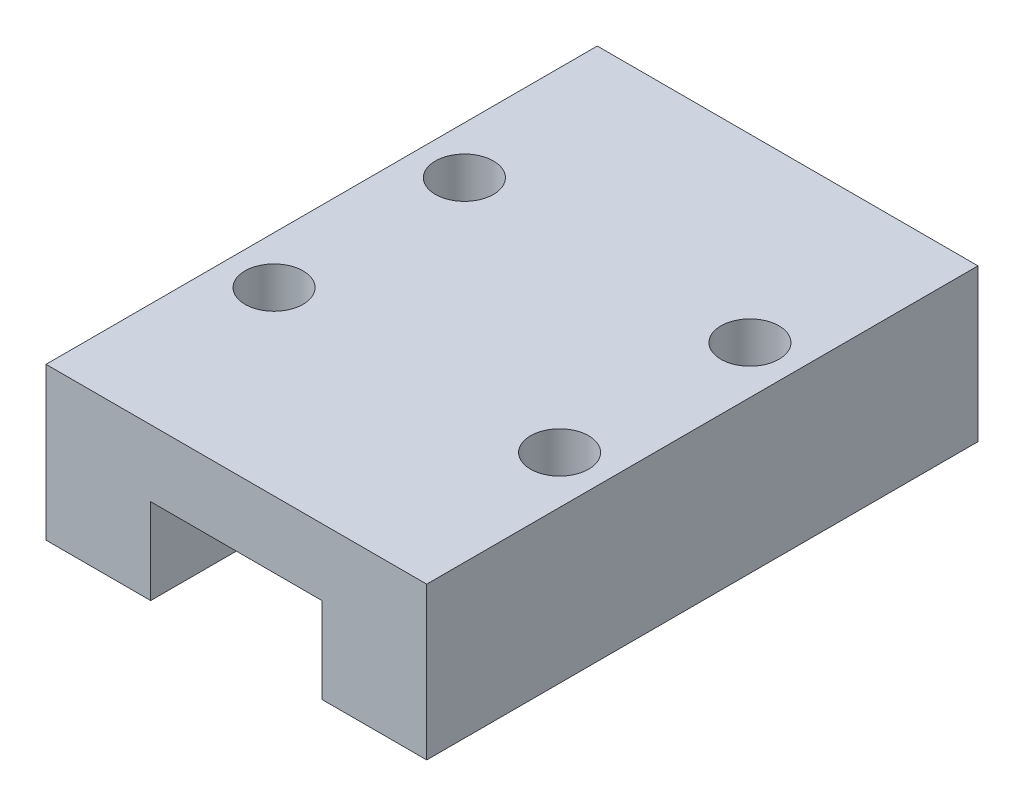
SolidWorks part; units mm, degrees
ref_plane "前视基准面" through (0, 0, 0) normal (0, 0, 1) x (1, 0, 0)
ref_plane "上视基准面" through (0, 0, 0) normal (0, 1, 0) x (1, 0, 0)
ref_plane "右视基准面" through (0, 0, 0) normal (1, 0, 0) x (0, 0, -1)
other "Configuration Table"
sketch "草图1" plane through (0, 0, 0) normal (0, 0, 1) x (1, 0, 0)
  line L0 (0, 0) -> (0, 4.5) construction
  line L1 (0, 4.5) -> (0, 8) construction
  line L2 (-10, 8) -> (10, 8)
  line L3 (10, 8) -> (10, 0)
  line L4 (10, 0) -> (4.5, 0)
  line L5 (4.5, 0) -> (4.5, 4.5)
  line L6 (4.5, 4.5) -> (-4.5, 4.5)
  line L7 (0, 0) -> (4.5, 0) construction
  line L8 (-10, 8) -> (-10, 0)
  line L9 (-10, 0) -> (-4.5, 0)
  line L10 (-4.5, 0) -> (-4.5, 4.5)
  line L11 (-4.5, 0) -> (-4.5, -2) construction
  line L12 (-4.5, -2) -> (4.5, -2) construction
  line L13 (4.5, -2) -> (4.5, 0) construction
  dimension "D1" = 20
  dimension "D2" = 9
  dimension "D3" = 8
  dimension "D4" = 10
  dimension "D5" = 6.5
extrude "凸台-拉伸1" add sketch "草图1" along normal blind 28.96
sketch "草图2" plane through (0, 8, 0) normal (0, 1, 0) x (1, 0, 0)
  line L0 (0, 0) -> (0, -28.96) construction
  line L1 (10, -28.96) -> (-10, -28.96) construction
  line L2 (0, -14.48) -> (10, -14.48) construction
  line L3 (10, -28.96) -> (10, 0) construction
  circle A0 centre (7.5, -9.48) radius 1.525
  circle A1 centre (7.5, -19.48) radius 1.525
  circle A2 centre (-7.5, -19.48) radius 1.525
  circle A3 centre (-7.5, -9.48) radius 1.525
  dimension "D1" = 3.05
  dimension "D2" = 15
  dimension "D3" = 10
extrude "切除-拉伸1" cut sketch "草图2" against normal blind 3
